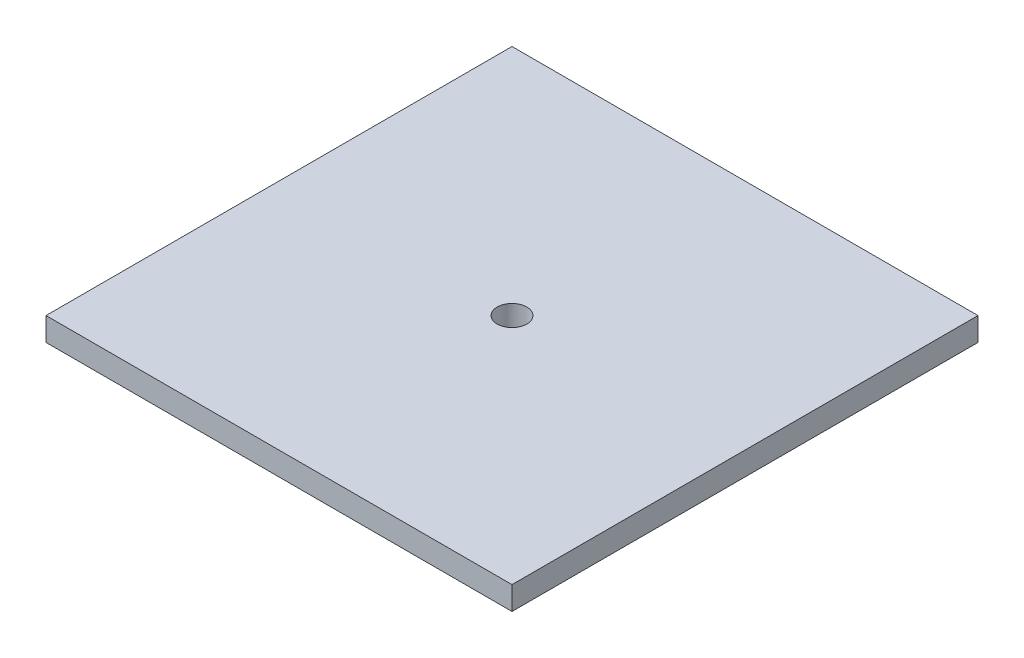
SolidWorks part; units mm, degrees
ref_plane "Front Plane" through (0, 0, 0) normal (0, 0, 1) x (1, 0, 0)
ref_plane "Top Plane" through (0, 0, 0) normal (0, 1, 0) x (1, 0, 0)
ref_plane "Right Plane" through (0, 0, 0) normal (1, 0, 0) x (0, 0, -1)
sketch "Sketch1" plane through (0, 0, 0) normal (0, 1, 0) x (1, 0, 0)
  line L1 (50, -50) -> (-50, -50)
  line L2 (50, -50) -> (50, 50)
  line L3 (50, 50) -> (-50, 50)
  line L4 (-50, -50) -> (-50, 50)
  line L5 (50, -50) -> (-50, 50) construction
  line L6 (50, 50) -> (-50, -50) construction
  circle A0 centre (0, 0) radius 3.175
  point P0 (0, 0)
  dimension "D3" = 6.35
  dimension "D1" = 100
  dimension "D2" = 100
extrude "Boss-Extrude1" add sketch "Sketch1" along normal blind 5
